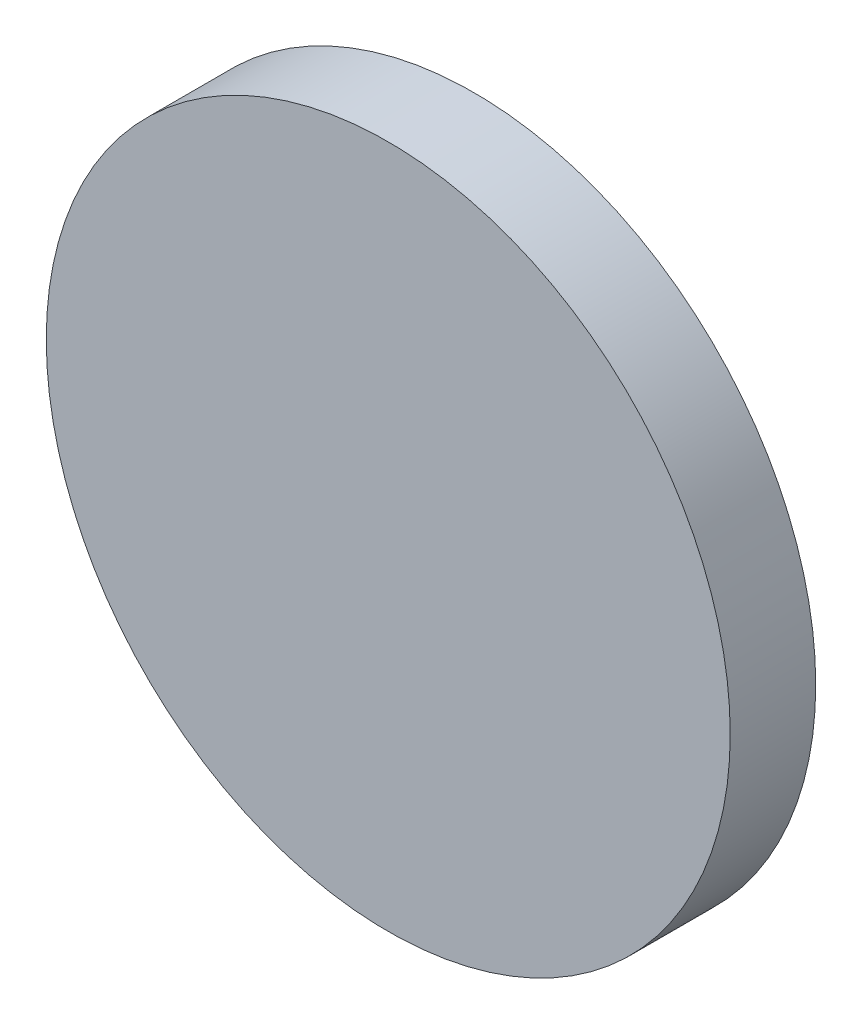
SolidWorks part; units mm, degrees
ref_plane "Plan de face" through (0, 0, 0) normal (0, 0, 1) x (1, 0, 0)
ref_plane "Plan de dessus" through (0, 0, 0) normal (0, 1, 0) x (1, 0, 0)
ref_plane "Plan de droite" through (0, 0, 0) normal (1, 0, 0) x (0, 0, -1)
sketch "Esquisse1" plane through (0, 0, 0) normal (0, 0, 1) x (1, 0, 0)
  circle A0 centre (0, 0) radius 25.4
extrude "Boss.-Extru.1" add sketch "Esquisse1" along normal blind 6.35
